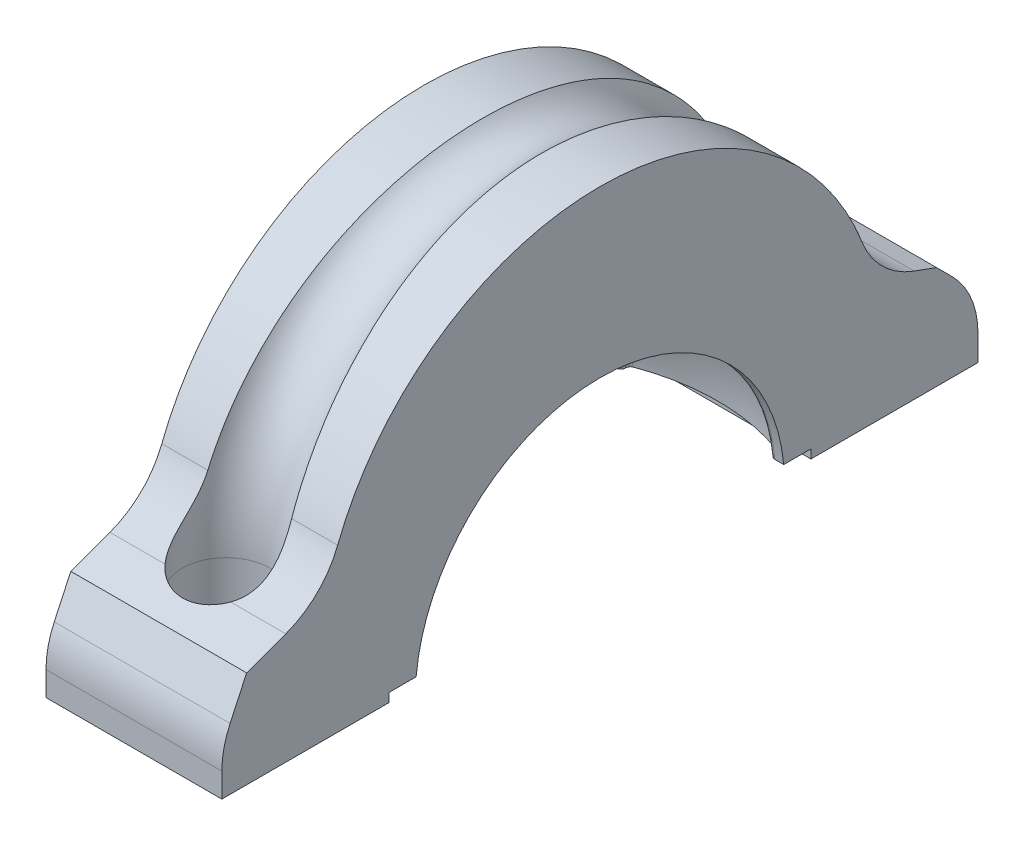
SolidWorks part; units mm, degrees
ref_plane "Front Plane" through (0, 0, 0) normal (0, 0, 1) x (1, 0, 0)
ref_plane "Top Plane" through (0, 0, 0) normal (0, 1, 0) x (1, 0, 0)
ref_plane "Right Plane" through (0, 0, 0) normal (1, 0, 0) x (0, 0, -1)
sketch "Sketch1" plane through (0, 0, 0) normal (1, 0, 0) x (0, 0, -1)
  line L0 (-86, 0) -> (-67, 0)
  line L1 (0, 0) -> (0, 10)
  line L2 (0, 10) -> (-11.8895, 14.3274)
  line L3 (-43, 17.5) -> (-43, 45.3769) construction
  line L4 (-86, 0) -> (-86, 10)
  line L5 (-86, 10) -> (-74.1105, 14.3274)
  line L6 (-19, 0) -> (-19, 1)
  line L8 (-67, 0) -> (-67, 1)
  line L10 (-19, 0) -> (0, 0)
  line L11 (-67, 1) -> (-19, 1)
  line L12 (-67, 0) -> (-19, 0) construction
  arc A1 (-74.1105, 14.3274) -> (-11.8895, 14.3274) centre (-43, 6.835) cw
  dimension "D1" = 32
  dimension "D2" = 86
  dimension "D3" = 10
  dimension "D4" = 70
  dimension "D6" = 1
  dimension "D8" = 19
  dimension "D9" = 43
extrude "Boss-Extrude1" add sketch "Sketch1" along normal blind 20
fillet "Fillet1" radius 10 2 edges at (10, 14.3274, 11.8895) (10, 14.3274, 74.1105)
chamfer "Chamfer1" distance 3 angle 45 2 edges at (10, 10, 0) (10, 10, 86)
fillet "Fillet2" [suppressed] radius 1
fillet "Fillet3" [suppressed] radius 1
ref_plane "Plane1" through (10, 0, 0) normal (1, 0, 0) x (0, 0, -1)
sketch "Sketch2" plane through (10, 0, 0) normal (1, 0, 0) x (0, 0, -1)
  line L1 (-10.5, -11.403) -> (-10.5, 10)
  line L4 (-43, -11.403) -> (-43, 46.1538) construction
  line L5 (-75.5, -11.403) -> (-75.5, 10)
  line L7 (-67, 1) -> (-19, 1) construction
  line L8 (-19, 0) -> (0, 0) construction
  arc A1 (-75.5, 10) -> (-10.5, 10) centre (-43, 10) cw
  point P12 (-43, 1)
  dimension "D2" = 32.5
  dimension "D1" = 65
  dimension "D3" = 10
ref_plane "Plane4" through (0, 0, 86) normal (0, 0, -1) x (-1, 0, 0)
ref_plane "Plane5" through (0, -11.403, 0) normal (0, -1, 0) x (-1, 0, 0)
sketch "Sketch5" plane through (0, -11.403, 0) normal (0, -1, 0) x (-1, 0, 0)
  circle A0 centre (-10, -10.5) radius 5
  dimension "D1" = 10
sweep "augu cut" cut profiles "Sketch5" path "Sketch2"
ref_plane "laagri center " through (0, -1, 0) normal (0, -1, 0) x (-1, 0, 0)
sketch "Sketch6" plane through (0, -1, 0) normal (0, -1, 0) x (1, 0, 0)
  line L0 (0, 64) -> (1.5, 64)
  line L2 (1.5, 64.9089) -> (1.5, 64)
  line L3 (0, 43) -> (20, 43)
  line L4 (18.5, 64.9089) -> (18.5, 64)
  line L5 (10, 10.5) -> (10, 75.5) construction
  line L7 (0, 67) -> (0, 19) construction
  line L8 (18.5, 64) -> (20, 64)
  line L9 (20, 67) -> (20, 19) construction
  line L10 (0, 64) -> (0, 43)
  line L12 (20, 64) -> (20, 43)
  arc A0 (1.5, 64.9089) -> (18.5, 64.9089) centre (10, 43) cw
  point P0 (10.2498, 50.9501)
  point P6 (10, 66.5)
  dimension "D2" = 23.5
  dimension "D1" = 17
  dimension "D3" = 21
  dimension "D4" = 1.5
  dimension "D5" = 1.5
  dimension "D6" = 0.9089
revolve "Cut-Revolve2" cut sketch "Sketch6" angle 360 about L3
sketch "Sketch8" plane through (0, -1, 0) normal (0, -1, 0) x (-1, 0, 0)
  line L0 (-30.4774, -7.5) -> (-30.4774, -72.5) construction
  line L3 (-30.4774, -40) -> (16.6094, -40) construction
fillet "Fillet4" radius 10 2 edges at (10, 4.9805, 86) (10, 7, 0)
fillet "Fillet5" radius 0.5 4 edges at (1.5, 20.9089, 43) (1.5, 20, 43) (18.5, 20, 43) (18.5, 20.9089, 43)
